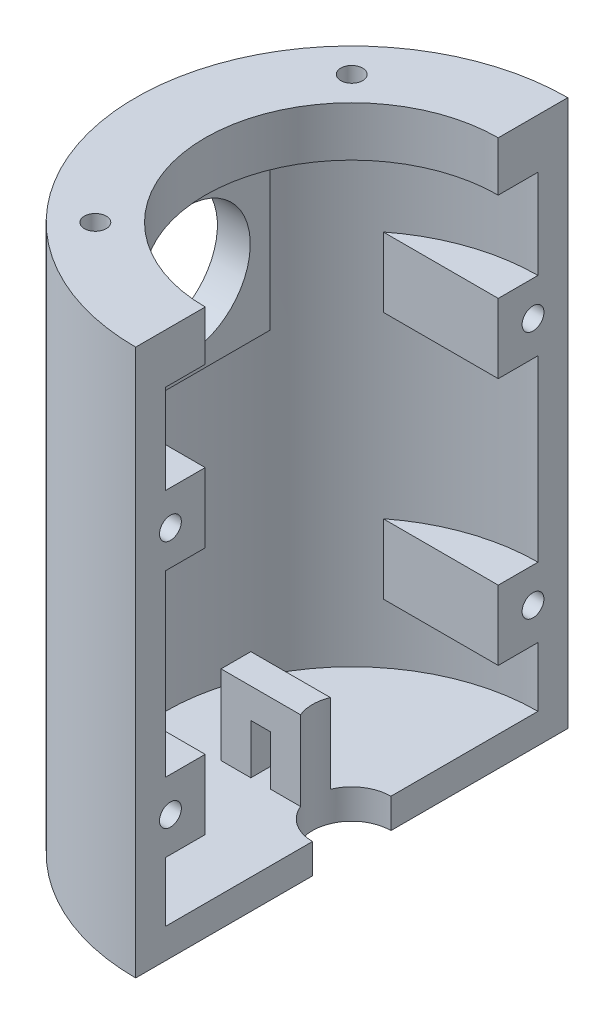
SolidWorks part; units mm, degrees
ref_plane "正面" through (0, 0, 0) normal (0, 0, 1) x (1, 0, 0)
ref_plane "平面" through (0, 0, 0) normal (0, 1, 0) x (1, 0, 0)
ref_plane "右側面" through (0, 0, 0) normal (1, 0, 0) x (0, 0, -1)
sketch "ｽｹｯﾁ1" plane through (0, 0, 0) normal (0, 1, 0) x (1, 0, 0)
  line L0 (0, -21.75) -> (0, -14.75)
  line L1 (0, -14.75) -> (0, 14.75) construction
  line L2 (0, 14.75) -> (0, 21.75)
  arc A0 (0, 21.75) -> (0, -21.75) centre (0, 0) ccw
  arc A1 (0, 14.75) -> (0, -14.75) centre (0, 0) ccw
  dimension "D1" = 14.75
  dimension "D2" = 7
extrude "ﾎﾞｽ - 押し出し1" add sketch "ｽｹｯﾁ1" along normal blind 55
sketch "ｽｹｯﾁ2" plane through (0, 55, 0) normal (0, 1, 0) x (1, 0, 0)
  circle A0 centre (0, 0) radius 14.75
  circle A1 centre (0, 0) radius 18.75
  arc A2 (0, 14.75) -> (0, -14.75) centre (0, 0) ccw construction
  arc A3 (0, 21.75) -> (0, -21.75) centre (0, 0) ccw construction
  dimension "D1" = 3
extrude "ｶｯﾄ - 押し出し1" cut sketch "ｽｹｯﾁ2" against normal through all from offset 5 offset against normal yes
sketch "ｽｹｯﾁ4" plane through (0, 0, 0) normal (1, 0, 0) x (0, 0, -1)
  line L0 (-14.75, 12.5) -> (-21.75, 12.5) construction
  line L1 (-21.75, 41) -> (-21.75, 34)
  line L2 (-18.75, 50) -> (-14.75, 50) construction
  line L3 (21.75, 55) -> (21.75, 0) construction
  line L4 (18.75, 50) -> (18.75, 0) construction
  line L5 (-21.75, 16) -> (-14.75, 16)
  line L6 (-14.75, 16) -> (-14.75, 9)
  line L7 (-14.75, 9) -> (-21.75, 9)
  line L8 (-21.75, 9) -> (-21.75, 16)
  line L9 (-21.75, 50) -> (21.75, 50) construction
  line L10 (0, 25) -> (-21.75, 25) construction
  line L11 (0, 25) -> (21.75, 25) construction
  line L12 (-21.75, 37.5) -> (21.75, 37.5) construction
  line L13 (-21.75, 0) -> (21.75, 0) construction
  line L14 (0, 50) -> (0, 0) construction
  line L15 (-18.25, 50) -> (-18.25, 0) construction
  line L16 (18.75, 50) -> (18.75, 37.5) construction
  line L17 (18.75, 37.5) -> (18.75, 25) construction
  line L18 (-21.75, 55) -> (-21.75, 0) construction
  line L19 (-21.75, 34) -> (-14.75, 34)
  line L20 (-14.75, 34) -> (-14.75, 41)
  line L21 (-14.75, 41) -> (-21.75, 41)
  line L22 (21.75, 9) -> (21.75, 16)
  line L23 (21.75, 16) -> (14.75, 16)
  line L24 (14.75, 16) -> (14.75, 9)
  line L25 (14.75, 9) -> (21.75, 9)
  line L26 (21.75, 34) -> (14.75, 34)
  line L27 (21.75, 41) -> (21.75, 34)
  line L28 (14.75, 41) -> (21.75, 41)
  line L29 (14.75, 34) -> (14.75, 41)
  circle A0 centre (-18.25, 37.5) radius 1.1 construction
  circle A1 centre (18.25, 37.5) radius 1.1 construction
  circle A2 centre (18.25, 12.5) radius 1.1 construction
  circle A3 centre (-18.25, 12.5) radius 1.1 construction
  dimension "D1" = 2.2
  dimension "D2" = 3.5
  dimension "D3" = 7
  dimension "D4" = 7
extrude "ﾎﾞｽ - 押し出し3" add sketch "ｽｹｯﾁ4" against normal up to next
sketch "ｽｹｯﾁ3" plane through (0, 0, 0) normal (1, 0, 0) x (0, 0, -1)
  line L0 (-21.75, 50) -> (21.75, 50) construction
  line L1 (0, 25) -> (-21.75, 25) construction
  line L2 (0, 25) -> (21.75, 25) construction
  line L3 (-21.75, 55) -> (-21.75, 0) construction
  line L4 (-21.75, 37.5) -> (21.75, 37.5) construction
  line L5 (21.75, 55) -> (21.75, 0) construction
  line L6 (-21.75, 0) -> (21.75, 0) construction
  line L7 (0, 50) -> (0, 0) construction
  line L8 (14.75, 50) -> (18.75, 50) construction
  line L9 (-18.25, 50) -> (-18.25, 0) construction
  line L10 (18.75, 50) -> (18.75, 37.5) construction
  line L11 (18.75, 37.5) -> (18.75, 25) construction
  line L12 (18.75, 50) -> (18.75, 41) construction
  circle A0 centre (-18.25, 37.5) radius 1.1
  circle A1 centre (18.25, 37.5) radius 1.1
  circle A2 centre (18.25, 12.5) radius 1.1
  circle A3 centre (-18.25, 12.5) radius 1.1
  dimension "D1" = 2.2
  dimension "D2" = 3.5
extrude "ｶｯﾄ - 押し出し2" cut sketch "ｽｹｯﾁ3" against normal blind 5
sketch "ｽｹｯﾁ5" plane through (0, 55, 0) normal (0, 1, 0) x (1, 0, 0)
  line L0 (0, 0) -> (-14.75, 0) construction
  line L1 (-14.75, 0) -> (-18.25, 0) construction
  line L2 (-18.25, 0) -> (-21.75, 0) construction
  line L3 (0, 0) -> (-12.9047, 12.9047) construction
  line L4 (-12.9047, -12.9047) -> (0, 0) construction
  circle A0 centre (0, 0) radius 18.25 construction
  arc A1 (0, 14.75) -> (0, -14.75) centre (0, 0) ccw construction
  arc A2 (0, 21.75) -> (0, -21.75) centre (0, 0) ccw construction
  circle A3 centre (-12.9047, -12.9047) radius 1.1
  circle A4 centre (-12.9047, 12.9047) radius 1.1
  dimension "D1" = 2.2
  dimension "D2" = 45
  dimension "D3" = 90
extrude "ｶｯﾄ - 押し出し3" cut sketch "ｽｹｯﾁ5" against normal up to vertex (5 mm away)
sketch "ｽｹｯﾁ6" plane through (0, 55, 0) normal (0, 1, 0) x (1, 0, 0)
  line L0 (-20.0203, 8.5) -> (-20.0203, -8.5)
  arc A0 (0, 21.75) -> (0, -21.75) centre (0, 0) ccw construction
  arc A1 (-20.0203, 8.5) -> (-20.0203, -8.5) centre (0, 0) ccw
  dimension "D1" = 17
extrude "ｶｯﾄ - 押し出し4" cut sketch "ｽｹｯﾁ6" against normal blind 17 from offset 5 offset against normal yes
sketch "ｽｹｯﾁ8" plane through (0, 50, 0) normal (0, -1, 0) x (1, 0, 0)
  line L0 (-16.7126, 8.5) -> (-16.7126, -8.5)
  arc A0 (-12.5377, -13.9417) -> (0, -18.75) centre (0, 0) ccw construction
  arc A1 (-16.7126, 8.5) -> (-16.7126, -8.5) centre (0, 0) ccw
  dimension "D1" = 17
extrude "ﾎﾞｽ - 押し出し4" add sketch "ｽｹｯﾁ8" along normal blind 17
sketch "ｽｹｯﾁ7" plane through (-20.0203, 0, 0) normal (-1, 0, 0) x (0, 0, 1)
  line L0 (8.5, 33) -> (-8.5, 50) construction
  line L2 (-8.5, 33) -> (8.5, 50) construction
  circle A0 centre (0, 41.5) radius 6.5
  dimension "D1" = 13
extrude "ｶｯﾄ - 押し出し5" cut sketch "ｽｹｯﾁ7" against normal through all
sketch "ｽｹｯﾁ9" plane through (0, 0, 0) normal (0, -1, 0) x (1, 0, 0)
  line L0 (0, 21.75) -> (0, 18.75) construction
  line L1 (0, -18.75) -> (0, -21.75) construction
  line L2 (0, 18.75) -> (0, -18.75) construction
  line L3 (0, 18.75) -> (0, 3.95)
  line L4 (0, -3.95) -> (0, -18.75)
  arc A0 (0, 18.75) -> (0, -18.75) centre (0, 0) ccw
  arc A1 (0, 18.75) -> (0, -18.75) centre (0, 0) ccw construction
  arc A2 (0, 3.95) -> (0, -3.95) centre (0, 0) ccw
  dimension "D1" = 3.95
extrude "ﾎﾞｽ - 押し出し5" add sketch "ｽｹｯﾁ9" against normal blind 3
sketch "ｽｹｯﾁ10" plane through (0, 3, 0) normal (0, 1, 0) x (1, 0, 0)
  line L1 (-3.6541, -1.5) -> (-11.6541, -1.5)
  line L2 (-11.6541, -1.5) -> (-11.6541, 1.5)
  line L3 (-11.6541, 1.5) -> (-3.6541, 1.5)
  arc A7 (-3.6541, -1.5) -> (-3.6541, 1.5) centre (0, 0) cw
  arc A8 (0, 3.95) -> (0, -3.95) centre (0, 0) ccw construction
  point P10 (-3.95, 0)
  dimension "D1" = 8
  dimension "D2" = 3
extrude "ﾎﾞｽ - 押し出し6" add sketch "ｽｹｯﾁ10" along normal blind 8
sketch "ｽｹｯﾁ11" plane through (0, 0, 1.5) normal (0, 0, 1) x (1, 0, 0)
  line L0 (-11.6541, 3) -> (-3.6541, 3) construction
  line L1 (-8.6541, 3) -> (-6.6541, 3)
  line L2 (-8.6541, 3) -> (-8.6541, 8)
  line L3 (-8.6541, 8) -> (-6.6541, 8)
  line L4 (-6.6541, 3) -> (-6.6541, 8)
  point P6 (-7.6541, 3)
  dimension "D1" = 5
  dimension "D2" = 2
extrude "ｶｯﾄ - 押し出し6" cut sketch "ｽｹｯﾁ11" against normal up to next
